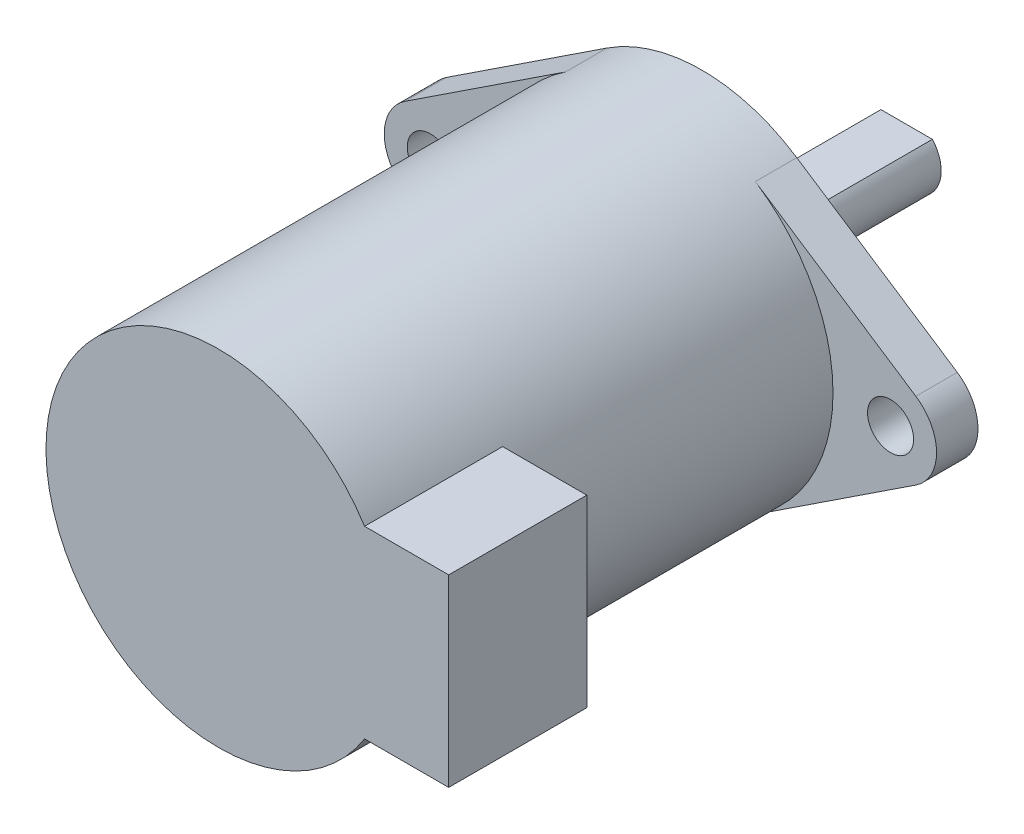
SolidWorks part; units mm, degrees
ref_plane "前视基准面" through (0, 0, 0) normal (0, 0, 1) x (1, 0, 0)
ref_plane "上视基准面" through (0, 0, 0) normal (0, 1, 0) x (1, 0, 0)
ref_plane "右视基准面" through (0, 0, 0) normal (1, 0, 0) x (0, 0, -1)
sketch "草图2" plane through (0, 0, 0) normal (0, 0, 1) x (1, 0, 0)
  circle A0 centre (0, 0) radius 7.5
  dimension "D1" = 15
extrude "凸台-拉伸2" add sketch "草图2" along normal blind 21
sketch "草图3" plane through (0, 0, 0) normal (0, 0, -1) x (-1, 0, 0)
  circle A0 centre (0, 0) radius 3
extrude "凸台-拉伸3" add sketch "草图3" along normal blind 2
sketch "草图4" plane through (0, 0, -2) normal (0, 0, -1) x (-1, 0, 0)
  circle A0 centre (0, 0) radius 1.5
extrude "凸台-拉伸4" add sketch "草图4" along normal blind 6.9
sketch "草图5" plane through (0, 0, -8.9) normal (0, 0, -1) x (-1, 0, 0)
  line L0 (-1.118, 1) -> (1.118, 1)
  circle A0 centre (0, 0) radius 1.5 construction
  arc A1 (1.118, 1) -> (-1.118, 1) centre (0, 0) ccw
  dimension "D1" = 1
extrude "切除-拉伸1" cut sketch "草图5" against normal blind 6.5
sketch "草图6" plane through (0, 0, 0) normal (0, 0, -1) x (-1, 0, 0)
  line L0 (11.1, 1.6703) -> (4.125, 6.2637)
  line L1 (11.1, -1.6703) -> (4.125, -6.2637)
  line L2 (0, 0) -> (0, 7.5) construction
  line L3 (-11.1, 1.6703) -> (-4.125, 6.2637)
  line L4 (-11.1, -1.6703) -> (-4.125, -6.2637)
  circle A0 centre (10, 0) radius 1
  arc A1 (4.125, 6.2637) -> (-4.125, 6.2637) centre (0, 0) ccw
  arc A2 (11.1, -1.6703) -> (11.1, 1.6703) centre (10, 0) ccw
  circle A3 centre (-10, 0) radius 1
  arc A4 (-11.1, -1.6703) -> (-11.1, 1.6703) centre (-10, 0) cw
  arc A5 (-4.125, -6.2637) -> (4.125, -6.2637) centre (0, 0) ccw
extrude "凸台-拉伸6" add sketch "草图6" against normal blind 1.8
sketch "草图7" plane through (0, 0, 0) normal (1, 0, 0) x (0, 0, -1)
  line L0 (-21, 7.5) -> (-21, -7.5) construction
  line L1 (-21, 4) -> (-15, 4)
  line L3 (-21, -4) -> (-15, -4)
  line L4 (-15, 4) -> (-15, -4)
  line L7 (-21, 4) -> (-21, -4)
  point P0 (-21, 0)
extrude "凸台-拉伸7" add sketch "草图7" along normal blind 10
